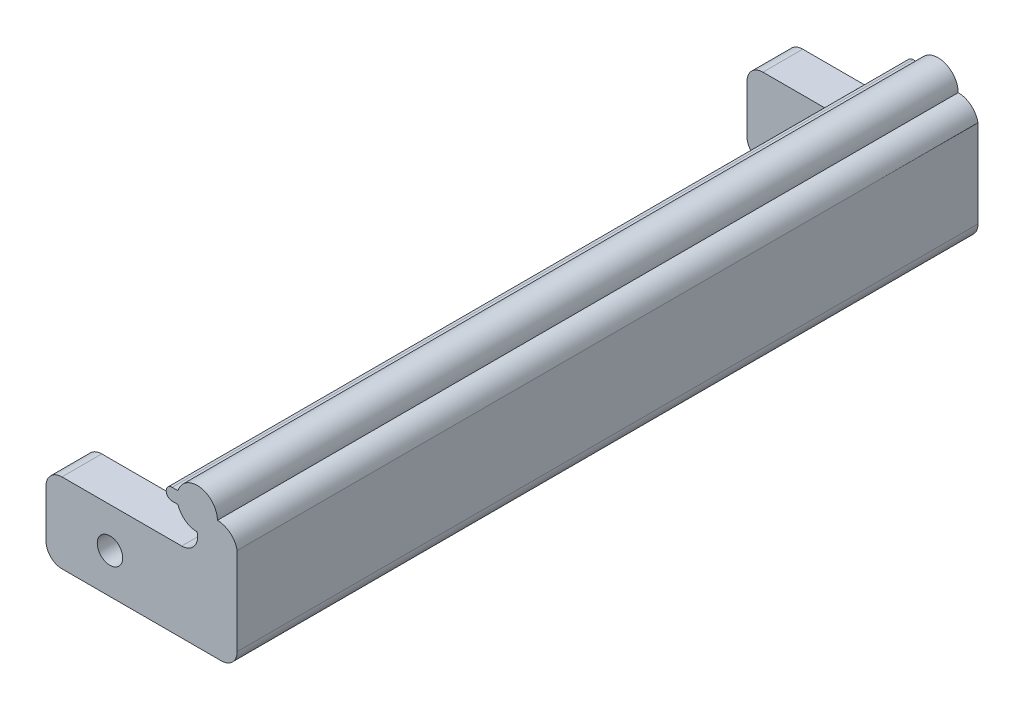
SolidWorks part; units mm, degrees
ref_plane "Front Plane" through (0, 0, 0) normal (0, 0, 1) x (1, 0, 0)
ref_plane "Top Plane" through (0, 0, 0) normal (0, 1, 0) x (1, 0, 0)
ref_plane "Right Plane" through (0, 0, 0) normal (1, 0, 0) x (0, 0, -1)
sketch "Sketch1" plane through (0, 0, 0) normal (0, 0, 1) x (1, 0, 0)
  line L0 (2, 10) -> (17.0335, 10)
  line L1 (0, 8) -> (0, 2)
  line L2 (2, 0) -> (22, 0)
  line L3 (24, 10) -> (24, 2)
  line L4 (24, 0) -> (20.2557, 0)
  line L5 (24, 0) -> (24, 13)
  circle A0 centre (8.0313, 5) radius 1.6
  arc A1 (0, 2) -> (2, 0) centre (2, 2) ccw
  arc A2 (2, 10) -> (0, 8) centre (2, 8) ccw
  arc A3 (22, 0) -> (24, 2) centre (22, 2) ccw
  arc A4 (19.0335, 12) -> (24, 13) centre (21.5167, 12.5) cw
  arc A7 (17.0335, 10) -> (19.0335, 12) centre (17.0335, 12) ccw
  point P7 (0, 5)
  point P17 (24, 6)
  point P20 (0, 0)
  point P23 (0, 10)
  point P32 (24, 15)
  point P35 (19.0335, 10)
  dimension "D1" = 3.2
  dimension "D10" = 3.2
  dimension "D13" = 2
  dimension "D14" = 2
  dimension "D3" = 24
  dimension "D4" = 10
  dimension "D5" = 15
  dimension "D8" = 19.0335
  dimension "D9" = 10
  dimension "D11" = 16
  dimension "D12" = 3.7443
extrude "Boss-Extrude1" add sketch "Sketch1" along normal blind 93
sketch "Sketch3" plane through (0, 15, 0) normal (0, 1, 0) x (1, 0, 0)
  line L0 (0, -93) -> (0, 0) construction
  line L1 (0, -5) -> (21.2678, -5)
  line L2 (0, -5) -> (0, -88)
  line L3 (0, -88) -> (21.2678, -88)
  line L4 (21.2678, -5) -> (21.2678, -88)
  line L6 (2, -93) -> (17.0335, -93) construction
  line L7 (2, 0) -> (17.0335, 0) construction
  dimension "D1" = 5
  dimension "D2" = 5
extrude "Cut-Extrude2" cut sketch "Sketch3" against normal blind 90
sketch "Sketch4" plane through (0, 0, 93) normal (0, 0, 1) x (1, 0, 0)
  line L0 (18.9837, 15.0331) -> (15.8461, 15.0331) construction
  line L1 (18.9837, 14.2776) -> (15.8461, 14.2776)
  line L2 (18.9837, 15.7886) -> (15.8461, 15.7886)
  line L4 (17.0335, 10) -> (2, 10)
  line L5 (0, 8) -> (0, 2)
  line L6 (2, 0) -> (22, 0)
  line L7 (24, 2) -> (24, 13)
  line L8 (17.0335, 10) -> (2, 10)
  line L9 (0, 8) -> (0, 2)
  line L10 (2, 0) -> (22, 0)
  line L11 (24, 2) -> (24, 13)
  arc A0 (18.9837, 12.5) -> (21.5167, 15.0331) centre (18.9837, 15.0331) cw
  arc A1 (24, 13) -> (19.0335, 12) centre (21.5167, 12.5) ccw construction
  arc A2 (24, 13) -> (21.5167, 15.0331) centre (21.5167, 12.5) ccw
  arc A3 (21.5167, 15.0331) -> (18.9837, 12.5) centre (21.5167, 12.5) ccw
  arc A4 (18.9837, 14.2776) -> (18.9837, 15.7886) centre (18.9837, 15.0331) ccw
  arc A5 (15.8461, 15.7886) -> (15.8461, 14.2776) centre (15.8461, 15.0331) ccw
  arc A7 (17.0335, 10) -> (19.0335, 12) centre (17.0335, 12) ccw
  arc A8 (2, 10) -> (0, 8) centre (2, 8) ccw
  arc A9 (0, 2) -> (2, 0) centre (2, 2) ccw
  arc A10 (22, 0) -> (24, 2) centre (22, 2) ccw
  arc A11 (24, 13) -> (19.0335, 12) centre (21.5167, 12.5) ccw
  arc A12 (17.0335, 10) -> (19.0335, 12) centre (17.0335, 12) ccw
  arc A13 (2, 10) -> (0, 8) centre (2, 8) ccw
  arc A14 (0, 2) -> (2, 0) centre (2, 2) ccw
  arc A15 (22, 0) -> (24, 2) centre (22, 2) ccw
  arc A16 (18.9837, 12.5) -> (19.0335, 12) centre (21.5167, 12.5) ccw
  point P9 (17.4149, 15.0331)
  dimension "D1" = 0
extrude "Boss-Extrude4" add sketch "Sketch4" against normal up to surface (93 mm away) up to face at (12.1741, 6.5172, 0)
